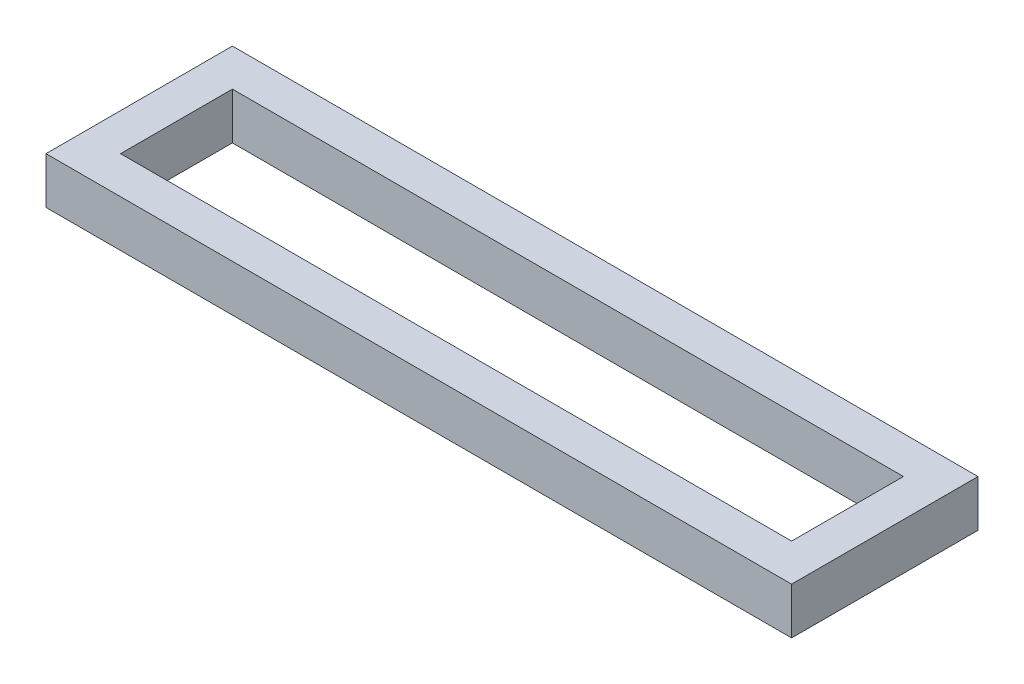
SolidWorks part; units mm, degrees
ref_plane "Front Plane" through (0, 0, 0) normal (0, 0, 1) x (1, 0, 0)
ref_plane "Top Plane" through (0, 0, 0) normal (0, 1, 0) x (1, 0, 0)
ref_plane "Right Plane" through (0, 0, 0) normal (1, 0, 0) x (0, 0, -1)
sketch "Sketch1" plane through (0, 0, 0) normal (0, 1, 0) x (1, 0, 0)
  line L0 (4, 4) -> (4, 16)
  line L1 (0, 0) -> (80, 0)
  line L2 (0, 0) -> (0, 20)
  line L3 (0, 20) -> (80, 20)
  line L4 (80, 0) -> (80, 20)
  line L5 (4, 16) -> (76, 16)
  line L6 (76, 4) -> (76, 16)
  line L7 (4, 4) -> (76, 4)
  dimension "D1" = 80
  dimension "D2" = 20
  dimension "D3" = 4
extrude "Boss-Extrude1" add sketch "Sketch1" along normal blind 5
